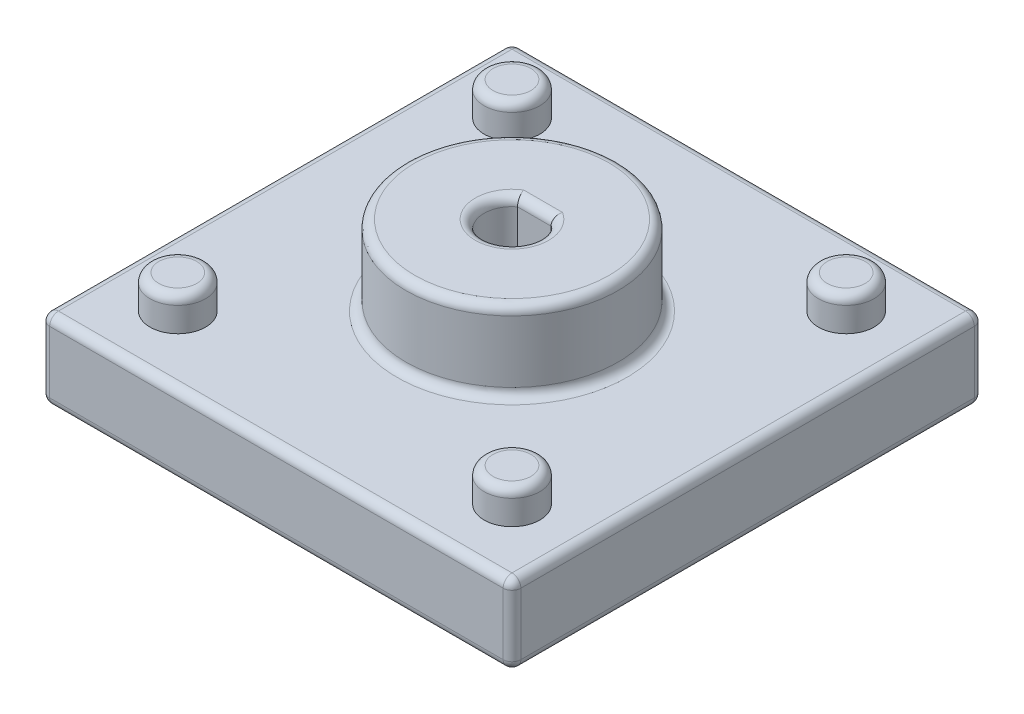
SolidWorks part; units mm, degrees
ref_plane "Front Plane" through (0, 0, 0) normal (0, 0, 1) x (1, 0, 0)
ref_plane "Top Plane" through (0, 0, 0) normal (0, 1, 0) x (1, 0, 0)
ref_plane "Right Plane" through (0, 0, 0) normal (1, 0, 0) x (0, 0, -1)
sketch "Sketch1" plane through (0, 0, 0) normal (0, 1, 0) x (1, 0, 0)
  line L0 (-1.5, 2) -> (1.5, 2)
  line L1 (0, -2.5) -> (9.1911, -2.5) construction
  circle A0 centre (0, 0) radius 9.525
  arc A1 (-1.5, 2) -> (1.5, 2) centre (0, 0) ccw
  arc A2 (1.5, 2) -> (-1.5, 2) centre (0, 0) ccw construction
  point P6 (9.1911, -2.5)
  dimension "D1" = 19.05
  dimension "D2" = 5
  dimension "D3" = 4.5
extrude "Boss-Extrude1" add sketch "Sketch1" along normal blind 14.2875
sketch "Sketch2" plane through (0, 0, 0) normal (0, 1, 0) x (1, 0, 0)
  line L1 (-21.15, -21.15) -> (21.15, -21.15)
  line L2 (-21.15, -21.15) -> (-21.15, 21.15)
  line L3 (-21.15, 21.15) -> (21.15, 21.15)
  line L4 (21.15, -21.15) -> (21.15, 21.15)
  line L5 (-21.15, -21.15) -> (21.15, 21.15) construction
  line L6 (-21.15, 21.15) -> (21.15, -21.15) construction
  circle A0 centre (0, 0) radius 9.525 construction
  circle A1 centre (0, 0) radius 9.525
  point P0 (0, 0)
  dimension "D1" = 42.3
extrude "Boss-Extrude2" add sketch "Sketch2" along normal blind 7.1437
sketch "Sketch3" plane through (0, 7.1437, 0) normal (0, 1, 0) x (1, 0, 0)
  line L1 (-15, -15) -> (15, -15) construction
  line L2 (-15, -15) -> (-15, 15) construction
  line L3 (-15, 15) -> (15, 15) construction
  line L4 (15, -15) -> (15, 15) construction
  line L5 (-15, -15) -> (15, 15) construction
  line L6 (-15, 15) -> (15, -15) construction
  circle A0 centre (-15, 15) radius 2.5
  circle A1 centre (15, 15) radius 2.5
  circle A2 centre (15, -15) radius 2.5
  circle A3 centre (-15, -15) radius 2.5
  point P0 (0, 0)
  dimension "D2" = 5
  dimension "D1" = 30
extrude "Boss-Extrude3" add sketch "Sketch3" along normal blind 3
fillet "Fillet1" radius 0.7937 22 edges at (-15, 10.1438, 17.5) (15, 10.1438, 17.5) (15, 10.1438, -12.5) (-15, 10.1438, -12.5) (0, 7.1437, 21.15) (0, 7.1437, -21.15) (21.15, 7.1437, 0) (-21.15, 7.1437, 0) (0, 0, -21.15) (0, 0, 21.15) (21.15, 0, 0) (-21.15, 0, 0) (21.15, 3.5719, 21.15) (-21.15, 3.5719, -21.15) (21.15, 3.5719, -21.15) (-21.15, 3.5719, 21.15) (0, 14.2875, 9.525) (0, 7.1437, -9.525) (0, 0, -2) (0, 14.2875, -2) (0, 0, 2.5) (0, 14.2875, 2.5)
